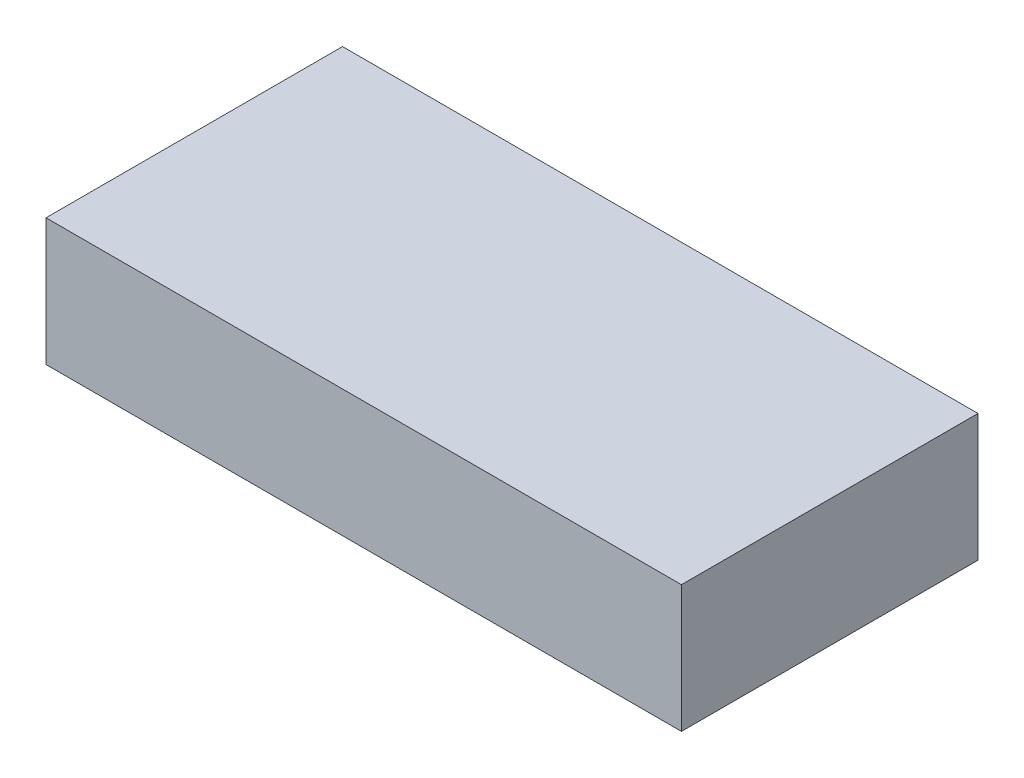
SolidWorks part; units mm, degrees
material "Hexcel AS4C (3000 Filaments)"
ref_plane "Front Plane" through (0, 0, 0) normal (0, 0, 1) x (1, 0, 0)
ref_plane "Top Plane" through (0, 0, 0) normal (0, 1, 0) x (1, 0, 0)
ref_plane "Right Plane" through (0, 0, 0) normal (1, 0, 0) x (0, 0, -1)
sketch "Sketch1" plane through (0, 0, 0) normal (0, 1, 0) x (1, 0, 0)
  line L1 (-40.4484, 18.296) -> (34.5516, 18.296)
  line L2 (-40.4484, 18.296) -> (-40.4484, -16.704)
  line L3 (-40.4484, -16.704) -> (34.5516, -16.704)
  line L4 (34.5516, 18.296) -> (34.5516, -16.704)
  dimension "D1" = 75
  dimension "D2" = 35
extrude "Boss-Extrude1" add sketch "Sketch1" along normal blind 15
